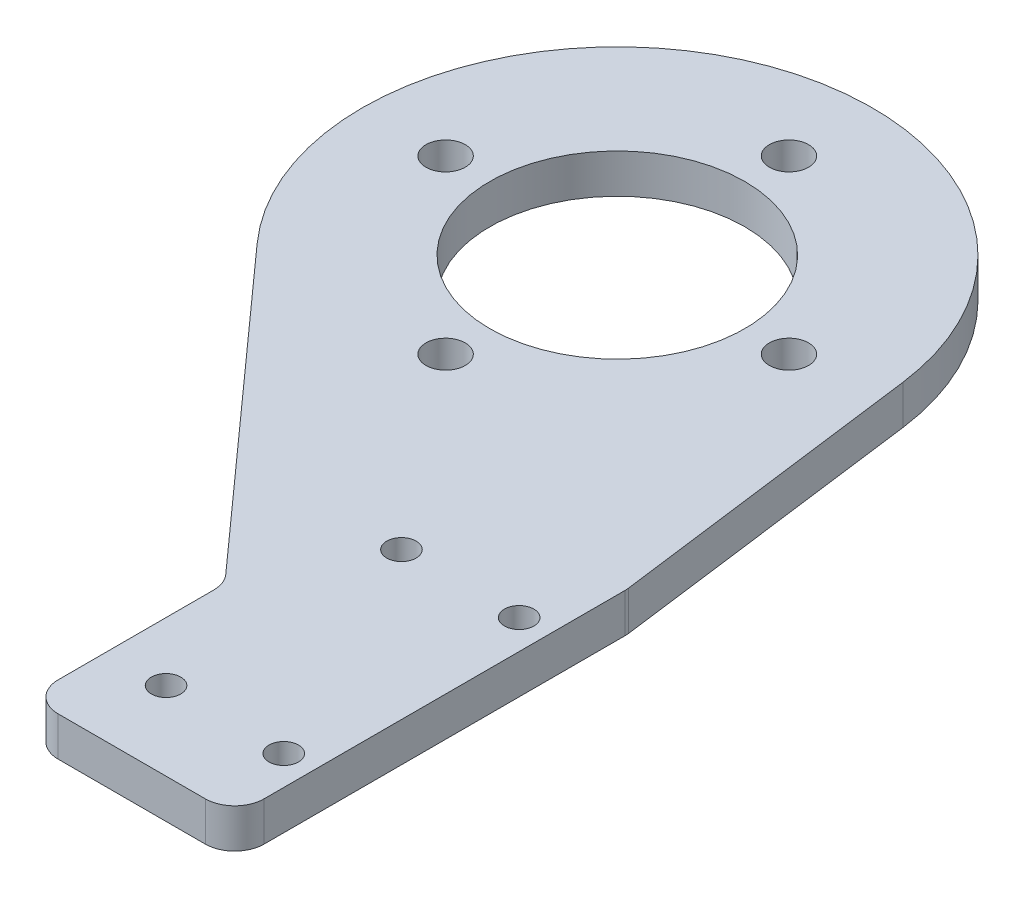
SolidWorks part; units mm, degrees
ref_plane "前视基准面" through (0, 0, 0) normal (0, 0, 1) x (1, 0, 0)
ref_plane "上视基准面" through (0, 0, 0) normal (0, 1, 0) x (1, 0, 0)
ref_plane "右视基准面" through (0, 0, 0) normal (1, 0, 0) x (0, 0, -1)
other "Configuration Table"
sketch "草图1" plane through (0, 0, 0) normal (0, 1, 0) x (1, 0, 0)
  line L0 (-15, 32) -> (-3, 32) construction
  line L1 (0, 0) -> (-21, 0)
  line L2 (0, 0) -> (0, 40)
  line L3 (0, 40) -> (-21, 40)
  line L4 (-21, 0) -> (-21, 40)
  line L5 (-15, 32) -> (-15, 8) construction
  line L6 (0, 40) -> (-4.2181, 72.3606)
  line L7 (-21, 20) -> (-49.3623, 51.6477)
  circle A0 centre (-15, 32) radius 1.5
  circle A1 centre (-3, 32) radius 1.5
  circle A2 centre (-3, 8) radius 1.5
  circle A3 centre (-15, 8) radius 1.5
  circle A4 centre (-30, 69) radius 21
  circle A5 centre (-30, 69) radius 26
  dimension "D3" = 3
  dimension "D4" = 8
  dimension "D5" = 6
  dimension "D11" = 42
  dimension "D14" = 5
  dimension "D1" = 40
  dimension "D2" = 21
  dimension "D8" = 90
  dimension "D9" = 12
  dimension "D10" = 24
  dimension "D12" = 37
  dimension "D13" = 15
  dimension "D6" = 2
  dimension "D7" = 2
extrude "凸台-拉伸1" add sketch "草图1" along normal blind 4 contours A5 A4 | A5 L7 L4 L3 L6 | L4 L1 L2 L3 A3 A2 A1 A0
sketch "草图2" plane through (0, 4, 0) normal (0, 1, 0) x (1, 0, 0)
  circle A0 centre (-30, 69) radius 13
  circle A1 centre (-12.5, 69) radius 2
  circle A2 centre (-30, 69) radius 21 construction
  circle A3 centre (-30, 69) radius 21
  circle A4 centre (-30, 51.5) radius 2
  circle A5 centre (-47.5, 69) radius 2
  circle A6 centre (-30, 86.5) radius 2
  dimension "D1" = 4
  dimension "D2" = 26
  dimension "D3" = 17.5
  dimension "D4" = 4
extrude "凸台-拉伸4" add sketch "草图2" against normal blind 4
fillet "圆角1" radius 3 4 edges at (0, 2, -40) (0, 2, 0) (-21, 2, 0) (-21, 2, -20)
